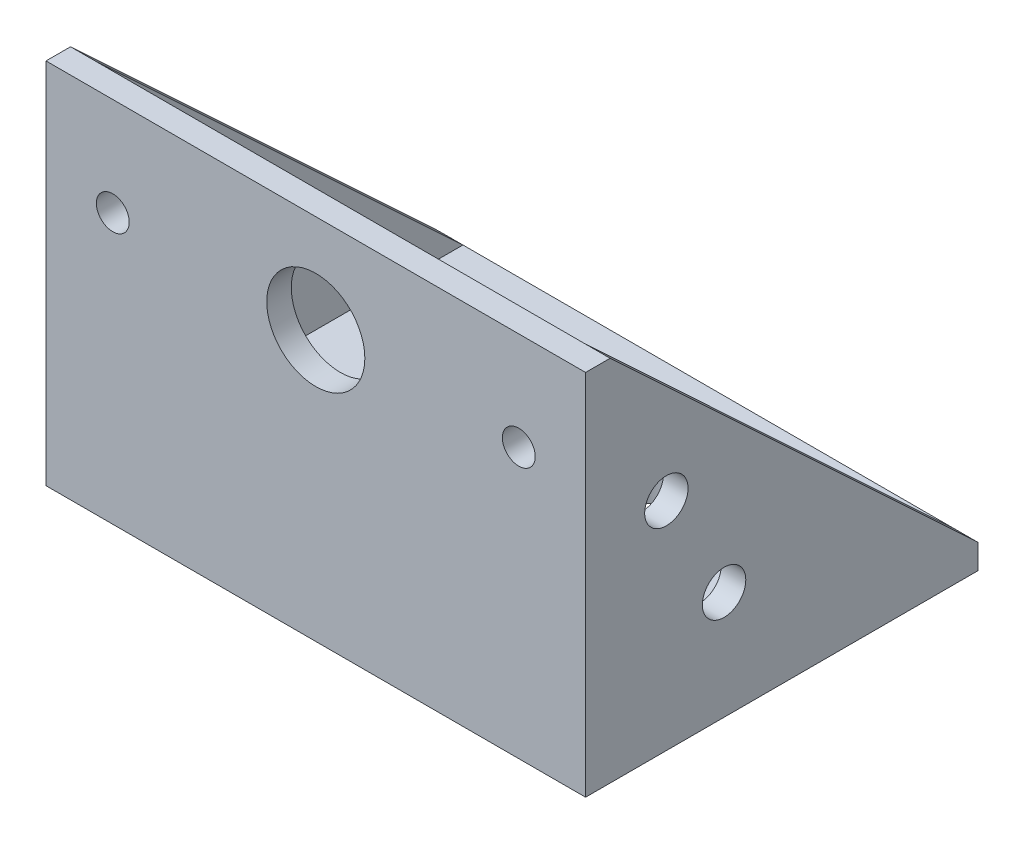
SolidWorks part; units mm, degrees
ref_plane "Front Plane" through (0, 0, 0) normal (0, 0, 1) x (1, 0, 0)
ref_plane "Top Plane" through (0, 0, 0) normal (0, 1, 0) x (1, 0, 0)
ref_plane "Right Plane" through (0, 0, 0) normal (1, 0, 0) x (0, 0, -1)
sketch "Sketch1" plane through (0, 0, 0) normal (0, 1, 0) x (1, 0, 0)
  line L0 (6.35, 25.4) -> (19.05, 25.4) construction
  line L1 (0, 0) -> (50.8, 0)
  line L2 (0, 0) -> (0, 38.1)
  line L3 (0, 38.1) -> (50.8, 38.1)
  line L4 (50.8, 0) -> (50.8, 38.1)
  circle A0 centre (6.35, 25.4) radius 2.2479
  circle A1 centre (19.05, 25.4) radius 2.2479
  circle A2 centre (31.75, 25.4) radius 2.2479
  circle A3 centre (44.45, 25.4) radius 2.2479
  dimension "D5" = 4
  dimension "D7" = 4.4958
  dimension "D1" = 38.1
  dimension "D2" = 50.8
  dimension "D3" = 25.4
  dimension "D4" = 6.35
  dimension "D6" = 12.7
extrude "Boss-Extrude1" add sketch "Sketch1" against normal blind 2.54
sketch "Sketch4" plane through (0, 0, 0) normal (0, 0, 1) x (1, 0, 0)
  line L1 (0, -2.54) -> (50.8, -2.54)
  line L2 (0, -2.54) -> (0, 35.56)
  line L3 (0, 35.56) -> (50.8, 35.56)
  line L4 (50.8, -2.54) -> (50.8, 35.56)
  line L5 (50.8, -2.54) -> (0, -2.54) construction
  line L7 (0, 25.4) -> (50.8, 25.4) construction
  circle A0 centre (25.4, 25.4) radius 5.08
  circle A1 centre (4.3764, 25.4) radius 1.7018
  circle A2 centre (46.4236, 25.4) radius 1.7018
  dimension "D3" = 10.16
  dimension "D6" = 3.4036
  dimension "D7" = 3.4036
  dimension "D1" = 38.1
  dimension "D2" = 25.4
  dimension "D4" = 25.4
  dimension "D5" = 21.0236
  dimension "D8" = 21.0236
extrude "Boss-Extrude2" add sketch "Sketch4" along normal blind 2.54
sketch "Sketch5" plane through (50.8, 0, 0) normal (1, 0, 0) x (0, 0, -1)
  line L0 (0, 35.56) -> (-2.54, 35.56)
  line L1 (-2.54, 35.56) -> (-2.54, -2.54)
  line L2 (-2.54, -2.54) -> (-2.54, 35.56) construction
  line L3 (-2.54, -2.54) -> (38.1, -2.54) construction
  line L4 (-2.54, -2.54) -> (38.1, -2.54)
  line L5 (38.1, -2.54) -> (38.1, 0)
  line L6 (38.1, 0) -> (0, 35.56)
  line L7 (17.78, -2.54) -> (-2.54, 35.56) construction
  circle A0 centre (11.8035, 8.6659) radius 2.2479
  circle A1 centre (5.8271, 19.8718) radius 2.2479
  dimension "D3" = 4.4958
  dimension "D4" = 4.4958
  dimension "D1" = 12.7
  dimension "D2" = 12.7
extrude "Boss-Extrude3" add sketch "Sketch5" along normal blind 2.54
sketch "Sketch6" plane through (0, 0, 0) normal (-1, 0, 0) x (0, 0, 1)
  line L0 (0, 35.56) -> (-38.1, 0)
  line L1 (-38.1, 0) -> (-38.1, -2.54)
  line L2 (-38.1, -2.54) -> (2.54, -2.54)
  line L3 (2.54, -2.54) -> (2.54, 35.56)
  line L4 (2.54, 35.56) -> (0, 35.56)
  line L5 (-17.78, -2.54) -> (2.54, 35.56) construction
  circle A0 centre (-11.8035, 8.6659) radius 2.2593
  circle A1 centre (-5.8271, 19.8718) radius 2.2479
  dimension "D3" = 4.5187
  dimension "D4" = 4.4958
  dimension "D1" = 12.7
  dimension "D2" = 12.7
extrude "Boss-Extrude4" add sketch "Sketch6" along normal blind 2.54
